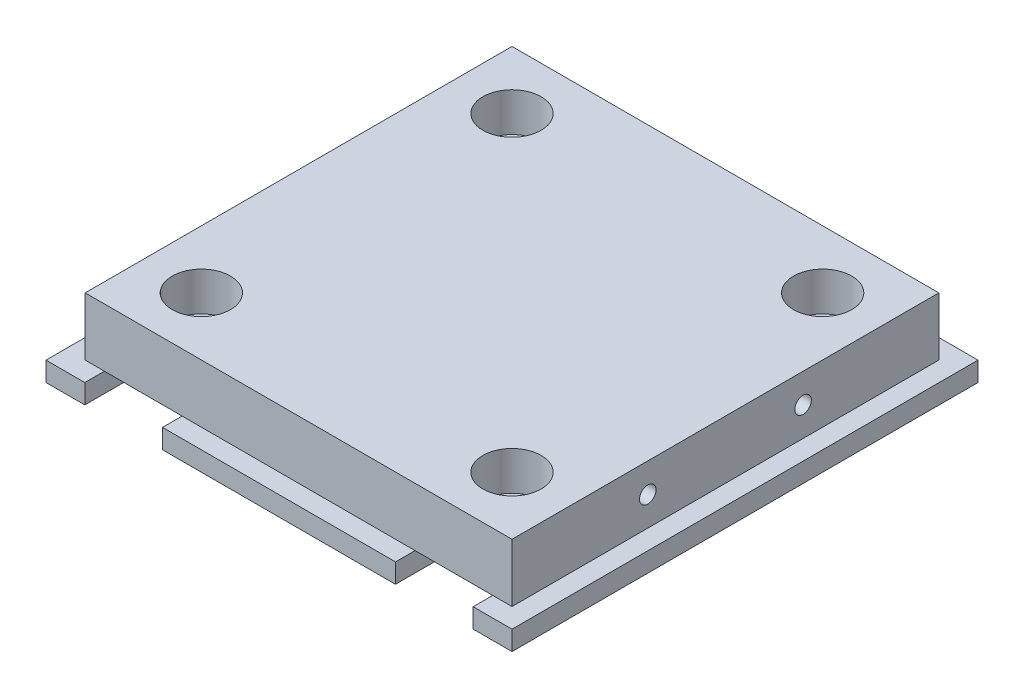
SolidWorks part; units mm, degrees
material "6061-T6 (SS)"
ref_plane "Front Plane" through (0, 0, 0) normal (0, 0, 1) x (1, 0, 0)
ref_plane "Top Plane" through (0, 0, 0) normal (0, 1, 0) x (1, 0, 0)
ref_plane "Right Plane" through (0, 0, 0) normal (1, 0, 0) x (0, 0, -1)
sketch "Sketch1" plane through (0, 0, 0) normal (0, 1, 0) x (1, 0, 0)
  line L1 (-38.1, -38.1) -> (38.1, -38.1)
  line L2 (-38.1, -38.1) -> (-38.1, 38.1)
  line L3 (-38.1, 38.1) -> (38.1, 38.1)
  line L4 (38.1, -38.1) -> (38.1, 38.1)
  line L5 (-38.1, -38.1) -> (38.1, 38.1) construction
  line L6 (-38.1, 38.1) -> (38.1, -38.1) construction
  point P0 (0, 0)
  dimension "D1" = 76.2
  dimension "D2" = 76.2
extrude "Boss-Extrude1" add sketch "Sketch1" along normal blind 3.175
sketch "Sketch2" plane through (0, 3.175, 0) normal (0, 1, 0) x (1, 0, 0)
  line L0 (-38.1, 38.1) -> (-38.1, -38.1) construction
  line L1 (34.8971, -34.8971) -> (-34.8971, -34.8971)
  line L2 (34.8971, -34.8971) -> (34.8971, 34.8971)
  line L3 (34.8971, 34.8971) -> (-34.8971, 34.8971)
  line L4 (-34.8971, -34.8971) -> (-34.8971, 34.8971)
  line L5 (34.8971, -34.8971) -> (-34.8971, 34.8971) construction
  line L6 (34.8971, 34.8971) -> (-34.8971, -34.8971) construction
  line L7 (28.5471, -28.5471) -> (-28.5471, -28.5471)
  line L8 (28.5471, -28.5471) -> (28.5471, 28.5471)
  line L9 (28.5471, 28.5471) -> (-28.5471, 28.5471)
  line L10 (-28.5471, -28.5471) -> (-28.5471, 28.5471)
  line L11 (28.5471, -28.5471) -> (-28.5471, 28.5471) construction
  line L12 (28.5471, 28.5471) -> (-28.5471, -28.5471) construction
  line L14 (38.1, 38.1) -> (-38.1, 38.1) construction
  point P0 (0, 0)
  point P6 (0, 0)
  dimension "D1" = 3.2029
  dimension "D2" = 3.2029
  dimension "D3" = 6.35
extrude "Boss-Extrude2" add sketch "Sketch2" along normal blind 9.525 contours L10 L7 L8 L9 | L4 L1 L2 L3 L7 L10 L9 L8
sketch "Sketch8" plane through (34.8971, 0, 0) normal (1, 0, 0) x (0, 0, -1)
  line L0 (-38.1, 3.175) -> (38.1, 3.175) construction
  point P0 (-12.7, 7.9375)
  dimension "D1" = 4.7625
  dimension "D2" = 12.7
hole_wizard "#6-32 Tapped Hole2" positions "Sketch10" profile "Sketch9" tap size "#6-32" standard "ANSI Inch"
sketch "Sketch10" plane through (34.8971, 0, 0) normal (1, 0, 0) x (0, 0, -1)
  point P0 (-12.7, 7.9375)
cosmetic thread "Hole Thread1" parameters "D1"=4.7346, "D2"=3.5052
sketch "Sketch9" plane through (34.8971, 7.9375, 12.7) normal (0, 1, 0) x (0, 0, -1)
  line L0 (0, 0) -> (0, 11.9887)
  line L1 (0, 11.9887) -> (1.3525, 11.176)
  line L2 (1.3525, 11.176) -> (1.3525, 0)
  line L5 (1.3525, 0) -> (0, 0)
  line L10 (0, 11.9887) -> (-1.3526, 11.176) construction
  line L11 (0, -6.35) -> (0, 107.95) construction
  dimension "Tap Drill Dia." = 2.7051
  dimension "Tap Drill Depth" = 11.176
  dimension "Drill Angle" = 118
mirror "Mirror1" about plane through (0, 0, 0) normal (0, 0, 1) of "#6-32 Tapped Hole2"
mirror "Mirror2" about plane through (0, 0, 0) normal (1, 0, 0) of "Mirror1", "#6-32 Tapped Hole2"
sketch "Sketch13" plane through (0, 0, 0) normal (0, -1, 0) x (1, 0, 0)
  line L0 (-38.1, 38.1) -> (38.1, 38.1) construction
  line L1 (-31.75, 38.1) -> (-19.05, 38.1)
  line L2 (-31.75, 38.1) -> (-31.75, -38.1)
  line L3 (-31.75, -38.1) -> (-19.05, -38.1)
  line L4 (-19.05, 38.1) -> (-19.05, -38.1)
  line L5 (38.1, -38.1) -> (-38.1, -38.1) construction
  line L6 (38.1, 38.1) -> (38.1, -38.1) construction
  line L7 (19.05, 38.1) -> (31.75, 38.1)
  line L8 (19.05, 38.1) -> (19.05, -38.1)
  line L9 (19.05, -38.1) -> (31.75, -38.1)
  line L10 (31.75, 38.1) -> (31.75, -38.1)
  line L11 (-38.1, -38.1) -> (-38.1, 38.1) construction
  line M2 (38.1, 38.1) -> (-38.1, 38.1)
  line M4 (-38.1, -38.1) -> (38.1, -38.1)
  dimension "D1" = 12.7
  dimension "D2" = 12.7
  dimension ".25" = 6.35
  dimension "D4" = 6.35
extrude "Cut-Extrude1" cut sketch "Sketch13" against normal blind 3.175 contours L4 L2 M2 M4 | L10 L8 M2 M4
sketch "Sketch15" plane through (0, 3.175, 0) normal (0, -1, 0) x (1, 0, 0)
  line L0 (-31.75, 34.8971) -> (-31.75, -34.8971) construction
  line L1 (31.75, 34.8971) -> (31.75, -34.8971) construction
  circle A0 centre (-25.4, 25.4) radius 2.5527
  circle A1 centre (25.4, 25.4) radius 2.5527
  circle A2 centre (25.4, -25.4) radius 2.5527
  circle A3 centre (-25.4, -25.4) radius 2.5527
  point P0 (25.4, 25.4)
  point P1 (25.4, -25.4)
  point P2 (-25.4, 25.4)
  point P3 (-25.4, -25.4)
  dimension "D5" = 5.1054
  dimension "D1" = 25.4
  dimension "D2" = 25.4
  dimension "D3" = 6.35
  dimension "D4" = 6.35
extrude "Cut-Extrude2" cut sketch "Sketch15" against normal through all
sketch "Sketch17" plane through (0, 12.7, 0) normal (0, 1, 0) x (1, 0, 0)
  circle A0 centre (-25.4, 25.4) radius 4.7625
  circle A1 centre (25.4, 25.4) radius 4.7625
  circle A2 centre (25.4, -25.4) radius 4.7625
  circle A3 centre (-25.4, -25.4) radius 4.7625
  dimension "D1" = 9.525
extrude "Cut-Extrude3" cut sketch "Sketch17" against normal blind 6.35
equation "\"D2@Sketch2\"=\"D1@Sketch2\""
equation "\"D2@Sketch1\"=\"D1@Sketch1\""
